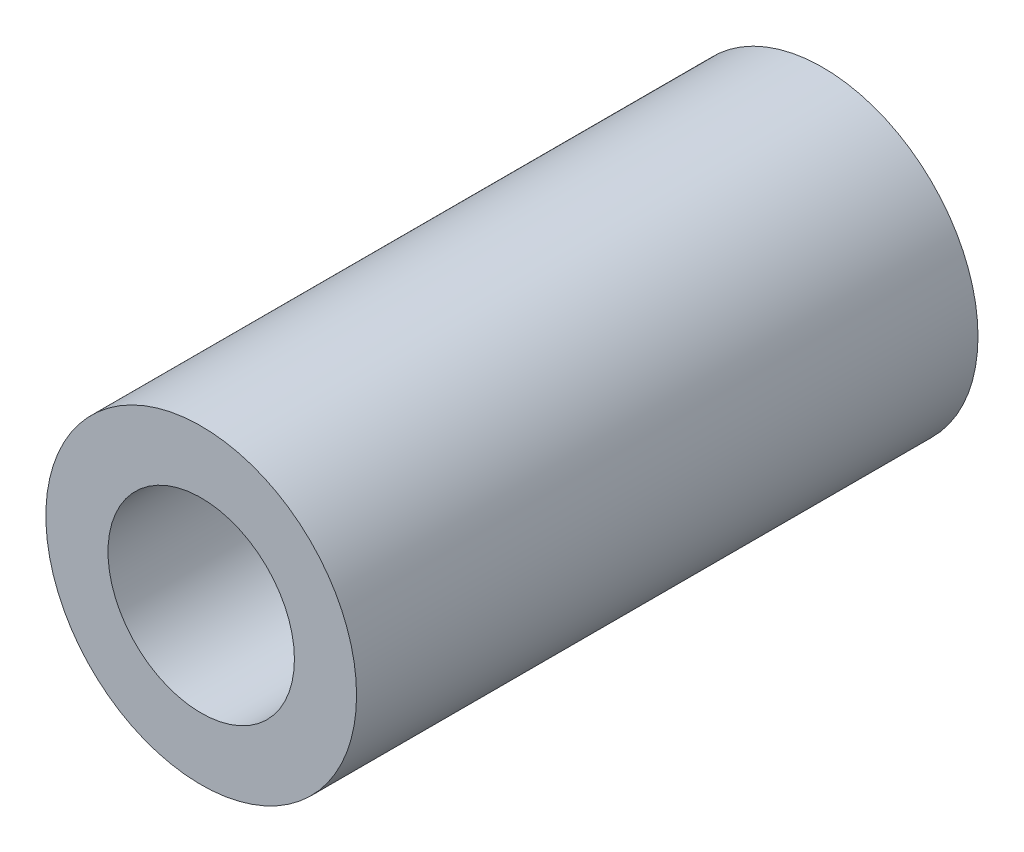
SolidWorks part; units mm, degrees
ref_plane "前视基准面" through (0, 0, 0) normal (0, 0, 1) x (1, 0, 0)
ref_plane "上视基准面" through (0, 0, 0) normal (0, 1, 0) x (1, 0, 0)
ref_plane "右视基准面" through (0, 0, 0) normal (1, 0, 0) x (0, 0, -1)
sketch "草图1" plane through (0, 0, 0) normal (0, 0, 1) x (1, 0, 0)
  circle A0 centre (0, 0) radius 4.5
  circle A1 centre (0, 0) radius 7.5
extrude "凸台-拉伸1" add sketch "草图1" along normal mid plane 30
